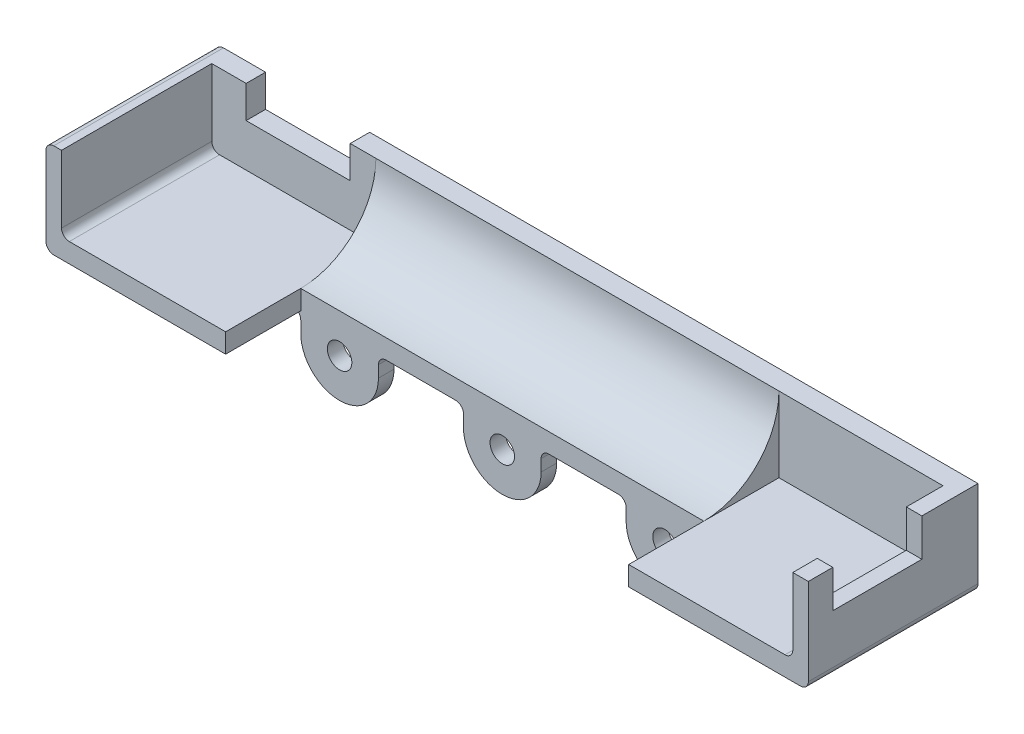
SolidWorks part; units mm, degrees
material "ABS"
ref_plane "X-Y Datum" through (0, 0, 0) normal (0, 0, 1) x (1, 0, 0)
ref_plane "X-Z Datum" through (0, 0, 0) normal (0, 1, 0) x (1, 0, 0)
ref_plane "Y-Z Datum" through (0, 0, 0) normal (1, 0, 0) x (0, 0, -1)
sketch "Sketch1" plane through (0, 0, 0) normal (1, 0, 0) x (0, 0, -1)
  line L1 (34.2074, 10.3366) -> (37.3824, 10.3366)
  line L4 (37.3824, 10.3366) -> (37.3824, -5.1193)
  line L5 (37.3824, -5.1193) -> (21.9265, -5.1193)
  line L6 (21.9265, -5.1193) -> (21.9265, -1.9443)
  arc A0 (21.9265, -1.9443) -> (34.2074, 10.3366) centre (21.9265, 10.3366) ccw
extrude "Boss-Extrude1" add sketch "Sketch1" along normal blind 65.8876
sketch "Sketch2" plane through (65.8876, 0, 0) normal (1, 0, 0) x (0, 0, -1)
  line L0 (37.3824, -1.9443) -> (37.3824, 10.3366)
  line L1 (37.3824, -5.1193) -> (9.6464, -5.1193)
  line L2 (37.3824, -5.1193) -> (37.3824, -1.9443)
  line L3 (34.2074, -1.9443) -> (9.6464, -1.9443)
  line L4 (9.6464, -5.1193) -> (9.6464, -1.9443)
  line L5 (37.3824, 10.3366) -> (34.2074, 10.3366)
  line L6 (34.2074, 10.3366) -> (34.2074, -1.9443)
extrude "Boss-Extrude2" add sketch "Sketch2" along normal blind 29.3624
sketch "Sketch3" plane through (95.25, 0, 0) normal (1, 0, 0) x (0, 0, -1)
  line L0 (28.2074, 4.1961) -> (13.6464, 4.1961)
  line L1 (34.2074, -1.9443) -> (28.2074, -1.9443)
  line L2 (34.2074, -1.9443) -> (34.2074, 10.3366)
  line L3 (34.2074, 10.3366) -> (28.2074, 10.3366)
  line L4 (28.2074, 4.1961) -> (28.2074, 10.3366)
  line L5 (9.6464, 4.1961) -> (9.6464, -1.9443)
  line L6 (9.6464, -1.9443) -> (28.2074, -1.9443)
  line L7 (9.6464, 4.1961) -> (9.6464, 10.3366)
  line L8 (9.6464, 10.3366) -> (13.6464, 10.3366)
  line L9 (13.6464, 10.3366) -> (13.6464, 4.1961)
extrude "Boss-Extrude3" add sketch "Sketch3" against normal blind 2.54
sketch "Sketch4" plane through (0, 0, -21.9265) normal (0, 0, 1) x (1, 0, 0)
  line L1 (0, -8.2943) -> (0, -5.1193)
  line L4 (12.7, -8.2943) -> (12.7, -5.1193)
  line L10 (12.7, -5.1193) -> (0, -5.1193)
  line L12 (32.9438, -5.1193) -> (32.9438, -8.2943) construction
  line L23 (0, -5.1193) -> (3.175, -5.1193) construction
  line L24 (65.8876, -5.1193) -> (0, -5.1193) construction
  line L27 (6.35, -5.1193) -> (6.35, -8.2943) construction
  line L30 (26.5938, -8.2943) -> (26.5938, -5.1193)
  line L31 (26.5938, -5.1193) -> (39.2938, -5.1193)
  line L32 (39.2938, -5.1193) -> (39.2938, -8.2943)
  line L33 (59.5376, -5.1193) -> (59.5376, -8.2943) construction
  line L34 (65.8876, -5.1193) -> (62.7126, -5.1193) construction
  line L35 (53.1876, -5.1193) -> (65.8876, -5.1193)
  line L36 (53.1876, -8.2943) -> (53.1876, -5.1193)
  line L37 (65.8876, -8.2943) -> (65.8876, -5.1193)
  arc A18 (0, -8.2943) -> (12.7, -8.2943) centre (6.35, -8.2943) ccw
  circle A19 centre (6.35, -8.2943) radius 2
  circle A20 centre (32.9438, -8.2943) radius 2
  arc A21 (26.5938, -8.2943) -> (39.2938, -8.2943) centre (32.9438, -8.2943) ccw
  circle A22 centre (59.5376, -8.2943) radius 2
  arc A23 (65.8876, -8.2943) -> (53.1876, -8.2943) centre (59.5376, -8.2943) cw
extrude "Boss-Extrude4" add sketch "Sketch4" against normal blind 2.54
ref_plane "Plane1" through (32.9438, 0, 0) normal (1, 0, 0) x (0, 0, -1)
mirror "Mirror1" about plane through (32.9438, 0, 0) normal (1, 0, 0) of "Boss-Extrude2"
sketch "Sketch6" plane through (-29.3624, 0, 0) normal (-1, 0, 0) x (0, 0, 1)
  line L0 (-9.6464, 10.3366) -> (-9.6464, -1.9443) construction
  line L1 (-34.2074, -1.9443) -> (-9.6464, -1.9443)
  line L2 (-34.2074, -1.9443) -> (-34.2074, 10.3366)
  line L3 (-34.2074, 10.3366) -> (-9.6464, 10.3366)
  line L4 (-9.6464, -1.9443) -> (-9.6464, 10.3366)
  line L5 (-13.6464, 10.3366) -> (-9.6464, 10.3366) construction
extrude "Boss-Extrude5" add sketch "Sketch6" against normal blind 2.54
sketch "Sketch7" plane through (0, 0, -37.3824) normal (0, 0, -1) x (-1, 0, 0)
  line L0 (29.3624, 10.3366) -> (29.3624, 8.7491) construction
  line L1 (29.3624, -5.1193) -> (29.3624, 10.3366) construction
  line L2 (29.3624, 8.7491) -> (20.701, 8.7491) construction
  line L3 (20.701, 8.7491) -> (20.701, 9.2571) construction
  line L4 (20.701, 8.7491) -> (21.209, 8.7491) construction
  line L10 (4.1935, 9.2571) -> (4.1935, 10.3366)
  line L13 (-95.25, 10.3366) -> (29.3624, 10.3366) construction
  line L15 (21.209, 9.2571) -> (21.209, 5.0661)
  line L16 (21.209, 5.0661) -> (4.1935, 5.0661)
  line L17 (4.1935, 9.2571) -> (4.1935, 5.0661)
  line L18 (4.1935, 10.3366) -> (21.209, 10.3366)
  line L19 (21.209, 10.3366) -> (21.209, 9.2571)
extrude "Cut-Extrude1" cut sketch "Sketch7" against normal through all
fillet "Fillet1" radius 1.27 3 edges at (-29.3624, -5.1193, -23.5144) (-29.3624, 10.3366, -23.5144) (95.25, -5.1193, -23.5144)
fillet "Fillet2" radius 1.27 6 edges at (12.7, -5.1193, -23.1965) (0, -5.1193, -23.1965) (26.5938, -5.1193, -23.1965) (39.2938, -5.1193, -23.1965) (53.1876, -5.1193, -23.1965) (65.8876, -5.1193, -23.1965)
fillet "Fillet4" radius 1.27 2 edges at (92.71, -1.9443, -21.9269) (-26.8224, -1.9443, -21.9269)
sketch "Sketch8" plane through (0, 0, -37.3824) normal (0, 0, -1) x (-1, 0, 0)
  circle A0 centre (-59.5376, -8.2943) radius 3.8
  circle A1 centre (-32.9438, -8.2943) radius 3.8
  circle A2 centre (-6.35, -8.2943) radius 3.8
extrude "Cut-Extrude2" cut sketch "Sketch8" against normal up to surface (12.9159 mm away) up to face at (57.5376, -8.2943, -24.4665)
